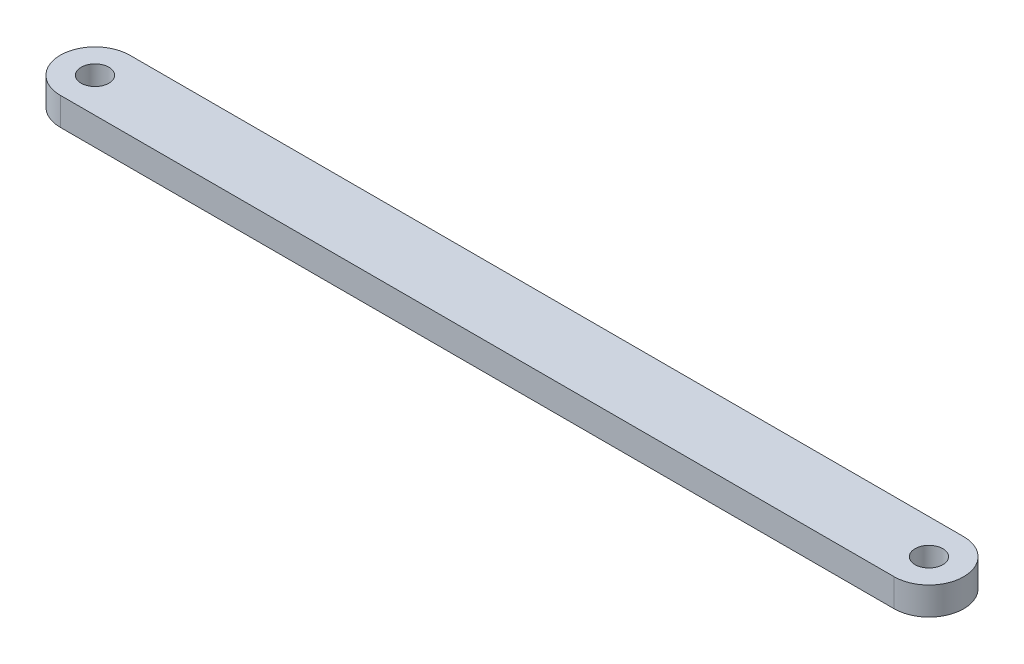
SolidWorks part; units mm, degrees
ref_plane "Front Plane" through (0, 0, 0) normal (0, 0, 1) x (1, 0, 0)
ref_plane "Top Plane" through (0, 0, 0) normal (0, 1, 0) x (1, 0, 0)
ref_plane "Right Plane" through (0, 0, 0) normal (1, 0, 0) x (0, 0, -1)
sketch "Sketch1" plane through (0, 0, 0) normal (0, 1, 0) x (1, 0, 0)
  line L0 (-10, 0) -> (50, 0) construction
  line L1 (-10, 2.5) -> (50, 2.5)
  line L2 (-10, -2.5) -> (50, -2.5)
  arc A0 (-10, 2.5) -> (-10, -2.5) centre (-10, 0) ccw
  arc A1 (50, -2.5) -> (50, 2.5) centre (50, 0) ccw
  circle A2 centre (50, 0) radius 1
  circle A3 centre (-10, 0) radius 1
  point P3 (20, 0)
  dimension "D3" = 2
  dimension "D4" = 2.5
  dimension "D5" = 2
  dimension "D1" = 60
  dimension "D12" = 10
extrude "Boss-Extrude1" add sketch "Sketch1" along normal blind 2
